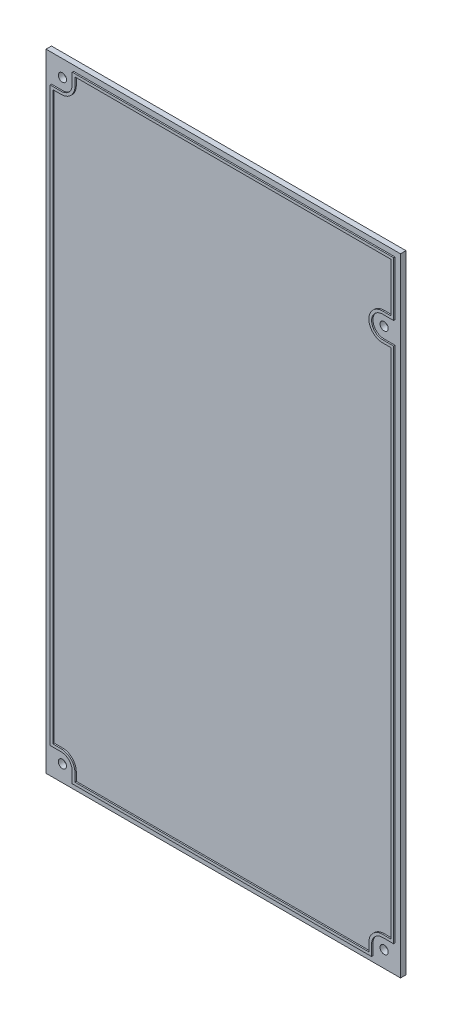
SolidWorks part; units mm, degrees
ref_plane "Front Plane" through (0, 0, 0) normal (0, 0, 1) x (1, 0, 0)
ref_plane "Top Plane" through (0, 0, 0) normal (0, 1, 0) x (1, 0, 0)
ref_plane "Right Plane" through (0, 0, 0) normal (1, 0, 0) x (0, 0, -1)
sketch "Sketch1" plane through (0, 0, 0) normal (0, 0, 1) x (1, 0, 0)
  line L1 (-65, -115) -> (65, -115)
  line L2 (-65, -115) -> (-65, 115)
  line L3 (-65, 115) -> (65, 115)
  line L4 (65, -115) -> (65, 115)
  line L5 (-65, -115) -> (65, 115) construction
  line L6 (-65, 115) -> (65, -115) construction
  point P0 (0, 0)
  dimension "D1" = 230
  dimension "D2" = 130
extrude "Boss-Extrude1" add sketch "Sketch1" along normal blind 2
sketch "Sketch2" plane through (0, 0, 2) normal (0, 0, 1) x (1, 0, 0)
  line L0 (65, -115) -> (65, 115) construction
  line L1 (-63, -113) -> (63, -113) construction
  line L2 (-63, -113) -> (-63, 113) construction
  line L3 (-63, 113) -> (63, 113) construction
  line L4 (63, -113) -> (63, 84.95) construction
  line L5 (-63, -113) -> (63, 113) construction
  line L6 (-63, 113) -> (63, -113) construction
  line L7 (65, 115) -> (-65, 115) construction
  line L8 (-63, -104.9) -> (-54.9, -113) construction
  line L9 (63, 93.05) -> (58.95, 93.05)
  line L11 (63, 84.95) -> (58.95, 84.95)
  line L13 (-63, 113) -> (-54.9, 113) construction
  line L14 (-63, 113) -> (-63, 104.9) construction
  line L15 (-63, 104.9) -> (-58.95, 104.9)
  line L16 (-54.9, 113) -> (-54.9, 108.95)
  line L17 (-63, -113) -> (-54.9, -113) construction
  line L18 (-63, -113) -> (-63, -104.9) construction
  line L19 (-63, -104.9) -> (-58.95, -104.9)
  line L20 (-54.9, -113) -> (-54.9, -108.95)
  line L21 (63, -113) -> (54.9, -113) construction
  line L22 (63, -113) -> (63, -104.9) construction
  line L23 (63, -104.9) -> (58.95, -104.9)
  line L24 (54.9, -113) -> (54.9, -108.95)
  line L25 (63, -104.9) -> (54.9, -113) construction
  line L26 (58.95, 93.05) -> (58.95, 84.95) construction
  line L27 (-54.9, 113) -> (-63, 104.9) construction
  line L28 (63, 84.95) -> (63, -104.9)
  line L29 (54.9, -113) -> (-54.9, -113)
  line L30 (-63, -104.9) -> (-63, 104.9)
  line L31 (-54.9, 113) -> (63, 113)
  line L32 (63, 113) -> (63, 93.05)
  line L33 (63, 93.05) -> (63, 113) construction
  circle A0 centre (-58.95, 108.95) radius 1.5 construction
  circle A1 centre (58.95, 89) radius 1.5 construction
  circle A2 centre (58.95, -108.95) radius 1.5 construction
  circle A3 centre (-58.95, -108.95) radius 1.5 construction
  arc A4 (-58.95, 104.9) -> (-54.9, 108.95) centre (-58.95, 108.95) ccw
  arc A5 (58.95, -104.9) -> (54.9, -108.95) centre (58.95, -108.95) ccw
  arc A6 (-58.95, -104.9) -> (-54.9, -108.95) centre (-58.95, -108.95) cw
  arc A7 (58.95, 93.05) -> (58.95, 84.95) centre (58.95, 89) ccw
  point P0 (0, 0)
  dimension "D12" = 3
  dimension "D13" = 4.05
  dimension "D1" = 2
  dimension "D2" = 2
  dimension "D3" = 8.1
  dimension "D4" = 8.1
  dimension "D5" = 8.1
  dimension "D6" = 4.05
  dimension "D7" = 8.1
  dimension "D8" = 8.1
  dimension "D9" = 8.1
  dimension "D10" = 8.1
  dimension "D11" = 19.95
extrude "Extrude-Thin1" add sketch "Sketch2" along normal blind 0.5 thin contours A7 L9 L32 L31 L16 A4 L15 L30 L19 A6 L20 L29 L24 A5 L23 L28 L11
sketch "Sketch3" plane through (0, 0, 2) normal (0, 0, 1) x (1, 0, 0)
  line L0 (58.95, 89) -> (59, 89) construction
  line L1 (58.95, 93.05) -> (58.95, 84.95) construction
  line L2 (63, 113) -> (63, 93.05) construction
  line L3 (-63, 113) -> (63, 113) construction
  line L5 (-63, -113) -> (-63, 113) construction
  line L6 (-63, -113) -> (63, -113) construction
  line L7 (63, -113) -> (63, 84.95) construction
  circle A0 centre (59, -109) radius 1.5
  circle A1 centre (-59, -109) radius 1.5
  circle A8 centre (-59, 109) radius 1.5
  circle A9 centre (59, 89) radius 1.5
  point P17 (-61.576, 107.2143)
  point P22 (0, 0)
  dimension "D1" = 3
  dimension "D2" = 4
  dimension "D3" = 4
  dimension "D4" = 4
  dimension "D5" = 4
  dimension "D6" = 4
  dimension "D7" = 4
  dimension "D8" = 4
extrude "Cut-Extrude1" cut sketch "Sketch3" against normal through all
